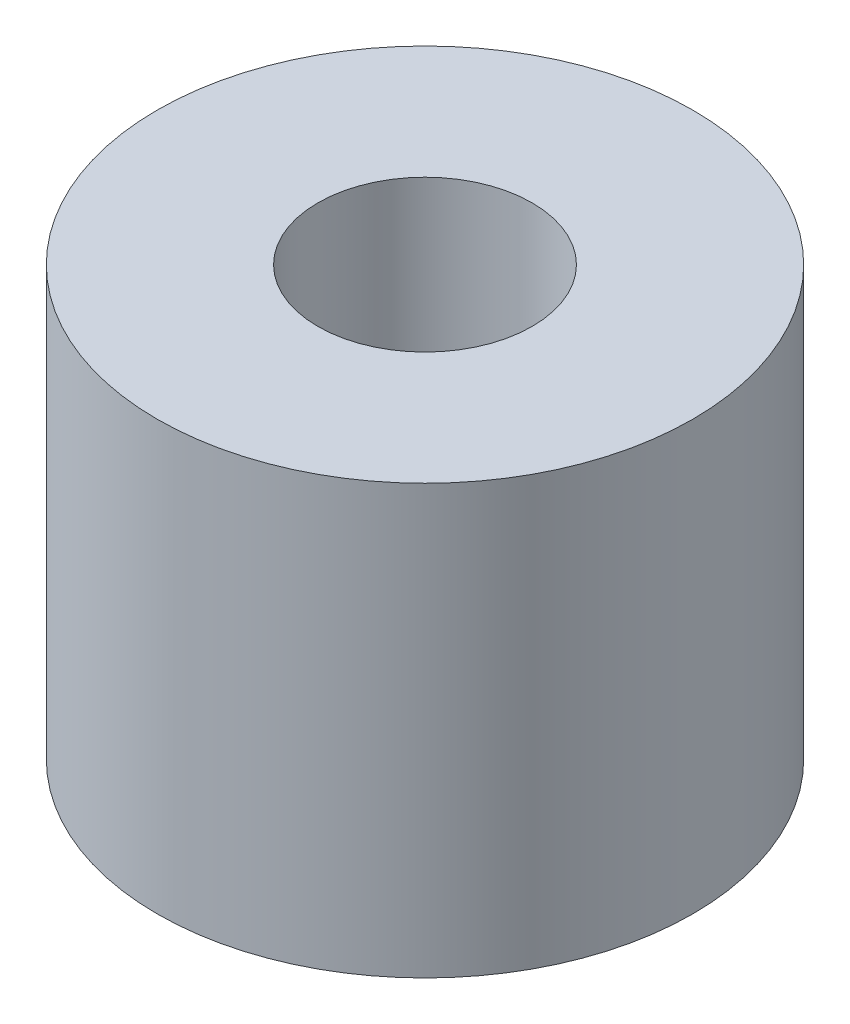
SolidWorks part; units mm, degrees
ref_plane "Спереди" through (0, 0, 0) normal (0, 0, 1) x (1, 0, 0)
ref_plane "Сверху" through (0, 0, 0) normal (0, 1, 0) x (1, 0, 0)
ref_plane "Справа" through (0, 0, 0) normal (1, 0, 0) x (0, 0, -1)
sketch "Эскиз1" plane through (0, 0, 0) normal (0, 1, 0) x (1, 0, 0)
  circle A0 centre (0, 0) radius 2
  circle A1 centre (0, 0) radius 5
  dimension "D1" = 4
  dimension "D2" = 10
extrude "Бобышка-Вытянуть1" add sketch "Эскиз1" along normal blind 8
